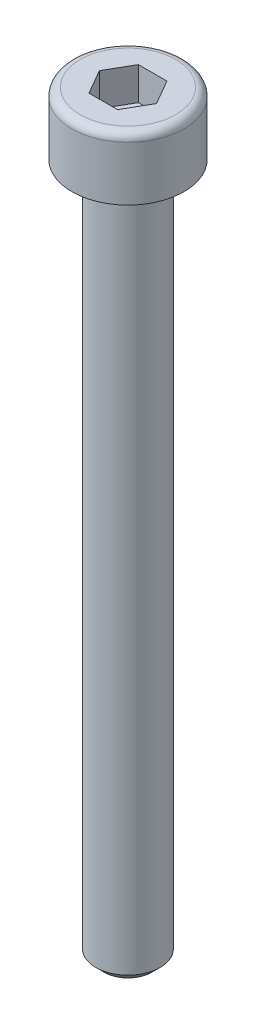
SolidWorks part; units mm, degrees
material "1023 Tôle d'acier au carbone (SS)"
ref_plane "Plan de face" through (0, 0, 0) normal (0, 0, 1) x (1, 0, 0)
ref_plane "Plan de dessus" through (0, 0, 0) normal (0, 1, 0) x (1, 0, 0)
ref_plane "Plan de droite" through (0, 0, 0) normal (1, 0, 0) x (0, 0, -1)
sketch "Esquisse1" plane through (0, 0, 0) normal (0, 0, 1) x (1, 0, 0)
  line L0 (0, 3.8) -> (0, -42) construction
  line L1 (0, 3.8) -> (-2.9, 3.8)
  line L2 (-3.4, 3.3) -> (-3.4, 0)
  line L3 (-3.4, 0) -> (-1.95, 0)
  line L4 (-1.95, 0) -> (-1.95, -41.5)
  line L5 (-1.95, -41.5) -> (-1.45, -42)
  line L6 (-1.45, -42) -> (0, -42)
  line L7 (0, 3.8) -> (0, -42)
  arc A0 (-2.9, 3.8) -> (-3.4, 3.3) centre (-2.9, 3.3) ccw
  point P11 (-1.95, -42)
  dimension "D5" = 0.5
  dimension "D1" = 3.9
  dimension "D2" = 6.8
  dimension "D3" = 42
  dimension "D4" = 3.8
  dimension "D8" = 0.5
revolve "Révolution1" add sketch "Esquisse1" angle 360 about L0
cosmetic thread "Représentation de filetage1" parameters "D2"=3.2
sketch "Esquisse2" plane through (0, 3.8, 0) normal (0, 1, 0) x (-1, 0, 0)
  line L1 (-1.7321, 0) -> (-0.866, -1.5)
  line L2 (-0.866, -1.5) -> (0.866, -1.5)
  line L3 (0.866, -1.5) -> (1.7321, 0)
  line L4 (1.7321, 0) -> (0.866, 1.5)
  line L5 (0.866, 1.5) -> (-0.866, 1.5)
  line L6 (-0.866, 1.5) -> (-1.7321, 0)
  circle A0 centre (0, 0) radius 1.5 construction
  dimension "D1" = 3
extrude "Enlèv. mat.-Extru.1" cut sketch "Esquisse2" against normal blind 2
